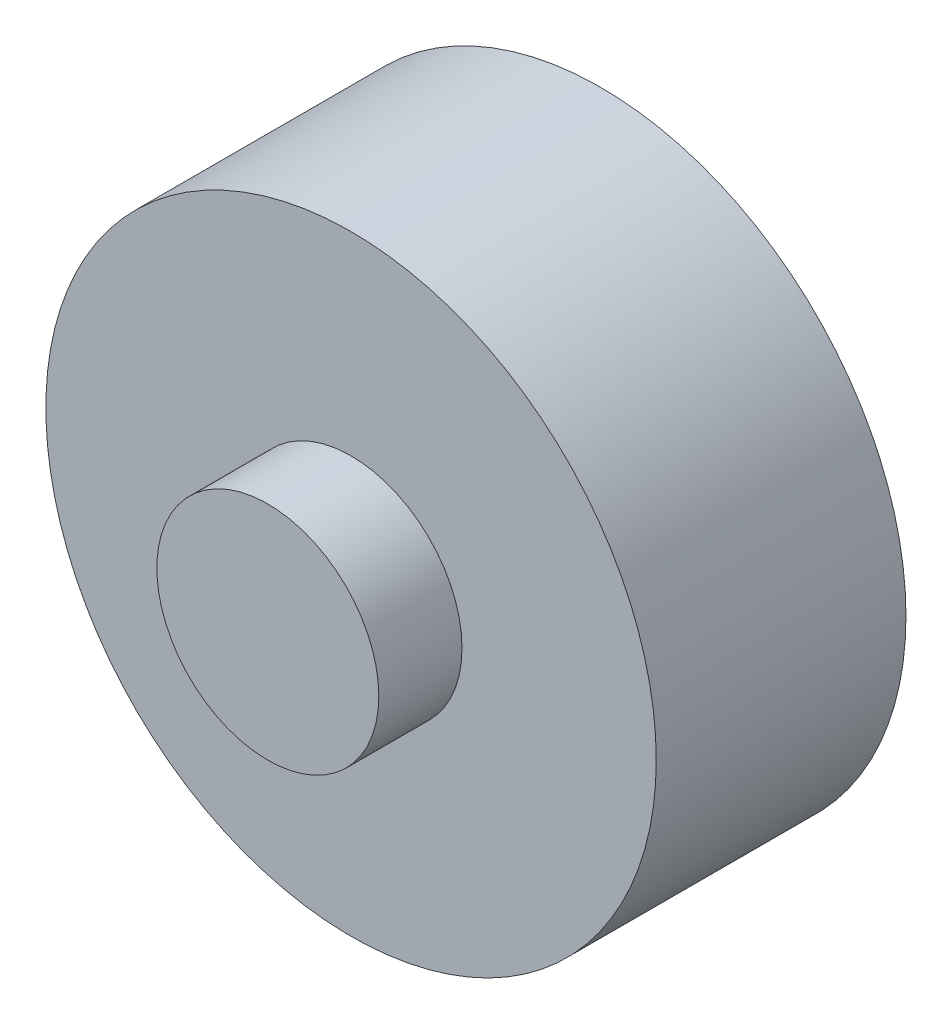
SolidWorks part; units mm, degrees
ref_plane "前视基准面" through (0, 0, 0) normal (0, 0, 1) x (1, 0, 0)
ref_plane "上视基准面" through (0, 0, 0) normal (0, 1, 0) x (1, 0, 0)
ref_plane "右视基准面" through (0, 0, 0) normal (1, 0, 0) x (0, 0, -1)
other "Configuration Table"
sketch "草图1" plane through (0, 0, 0) normal (0, 0, 1) x (1, 0, 0)
  circle A0 centre (0, 0) radius 8
extrude "凸台-拉伸1" add sketch "草图1" along normal blind 24
sketch "草图2" plane through (0, 0, 0) normal (0, 0, 1) x (1, 0, 0)
  circle A0 centre (0, 0) radius 22
extrude "凸台-拉伸2" add sketch "草图2" along normal blind 18
sketch "草图3" plane through (0, 0, 18) normal (0, 0, 1) x (1, 0, 0)
  line L0 (17.0755, 3.8312) -> (18.3379, 4.1145)
  line L1 (18.3379, 4.1145) -> (18.3903, 4.1291)
  line L2 (18.3903, 4.1291) -> (18.5441, 4.1833)
  line L3 (18.5441, 4.1833) -> (18.793, 4.2925)
  line L4 (18.793, 4.2925) -> (19.1289, 4.4711)
  line L5 (19.1289, 4.4711) -> (19.5423, 4.7328)
  line L6 (19.5423, 4.7328) -> (20.0218, 5.09)
  line L7 (20.0218, 5.09) -> (20.5548, 5.5539)
  line L8 (20.5548, 5.5539) -> (21.1275, 6.1342)
  line L9 (21.1275, 6.1342) -> (21.1275, 5.09)
  line L10 (21.1275, 5.09) -> (21.609, 4.1291)
  line L11 (21.609, 4.1291) -> (21.9022, 2.0722)
  line L12 (21.9022, 2.0722) -> (22, 0)
  line L13 (22, 0) -> (21.9511, 1.0361)
  line L14 (21.9511, 1.0361) -> (20.0218, 2.0722)
  line L15 (20.0218, 2.0722) -> (20.0483, 1.5377)
  line L16 (20.0483, 1.5377) -> (19.5743, 1.6589)
  line L17 (19.5743, 1.6589) -> (19.1996, 1.725)
  line L18 (19.1996, 1.725) -> (18.9292, 1.7519)
  line L19 (18.9292, 1.7519) -> (18.7662, 1.7559)
  line L20 (18.7662, 1.7559) -> (18.7119, 1.7536)
  line L21 (18.7119, 1.7536) -> (17.0755, 1.7536)
  line L22 (17.0755, 1.7536) -> (17.3629, 2.1864)
  line L23 (17.3629, 2.1864) -> (17.2845, 2.7376)
  line L24 (17.2845, 2.7376) -> (17.0755, 3.8312)
  line L25 (15.0558, 8.9203) -> (16.169, 9.5798)
  line L26 (16.169, 9.5798) -> (16.2143, 9.6099)
  line L27 (16.2143, 9.6099) -> (16.3438, 9.709)
  line L28 (16.3438, 9.709) -> (16.5467, 9.8897)
  line L29 (16.5467, 9.8897) -> (16.811, 10.1635)
  line L30 (16.811, 10.1635) -> (17.1233, 10.5401)
  line L31 (17.1233, 10.5401) -> (17.4689, 11.0279)
  line L32 (17.4689, 11.0279) -> (17.8325, 11.6338)
  line L33 (17.8325, 11.6338) -> (18.6723, 11.6338)
  line L34 (18.6723, 11.6338) -> (19.3108, 10.5401)
  line L35 (19.3108, 10.5401) -> (20.1104, 8.9203)
  line L36 (20.1104, 8.9203) -> (20.6981, 7.4557)
  line L37 (20.6981, 7.4557) -> (20.5406, 7.8482)
  line L38 (20.5406, 7.8482) -> (19.3108, 7.8482)
  line L39 (19.3108, 7.8482) -> (18.5919, 7.6577)
  line L40 (18.5919, 7.6577) -> (18.1037, 7.6265)
  line L41 (18.1037, 7.6265) -> (17.7269, 7.5735)
  line L42 (17.7269, 7.5735) -> (17.4614, 7.5156)
  line L43 (17.4614, 7.5156) -> (17.3051, 7.4691)
  line L44 (17.3051, 7.4691) -> (17.2541, 7.4501)
  line L45 (17.2541, 7.4501) -> (16.169, 7.4501)
  line L46 (16.169, 7.4501) -> (15.8375, 7.4448)
  line L47 (15.8375, 7.4448) -> (15.5926, 7.9448)
  line L48 (15.5926, 7.9448) -> (15.0558, 8.9203)
  line L49 (11.5624, 13.1362) -> (12.4173, 14.1075)
  line L50 (12.4173, 14.1075) -> (12.4511, 14.15)
  line L51 (12.4511, 14.15) -> (12.5436, 14.2843)
  line L52 (12.5436, 14.2843) -> (12.6808, 14.5189)
  line L53 (12.6808, 14.5189) -> (12.8476, 14.8609)
  line L54 (12.8476, 14.8609) -> (13.0281, 15.3156)
  line L55 (13.0281, 15.3156) -> (13.2061, 15.8864)
  line L56 (13.2061, 15.8864) -> (13.3647, 16.575)
  line L57 (13.3647, 16.575) -> (13.3647, 17.4753)
  line L58 (13.3647, 17.4753) -> (15.0558, 16.0413)
  line L59 (15.0558, 16.0413) -> (15.5563, 15.5563)
  line L60 (15.5563, 15.5563) -> (16.222, 14.8609)
  line L61 (16.222, 14.8609) -> (17.3811, 13.4869)
  line L62 (17.3811, 13.4869) -> (17.1062, 13.8128)
  line L63 (17.1062, 13.8128) -> (16.222, 13.8128)
  line L64 (16.222, 13.8128) -> (15.5563, 13.4869)
  line L65 (15.5563, 13.4869) -> (14.8609, 12.8476)
  line L66 (14.8609, 12.8476) -> (14.5189, 12.6808)
  line L67 (14.5189, 12.6808) -> (14.2843, 12.5436)
  line L68 (14.2843, 12.5436) -> (14.15, 12.4511)
  line L69 (14.15, 12.4511) -> (14.1075, 12.4173)
  line L70 (14.1075, 12.4173) -> (12.4173, 11.0279)
  line L71 (12.4173, 11.0279) -> (13.2624, 11.7226)
  line L72 (13.2624, 11.7226) -> (12.4173, 11.7226)
  line L73 (12.4173, 11.7226) -> (11.5624, 13.1362)
  line L74 (6.9372, 15.8864) -> (7.4501, 16.575)
  line L75 (7.4501, 16.575) -> (7.4691, 17.3051)
  line L76 (7.4691, 17.3051) -> (7.5156, 17.4614)
  line L77 (7.5156, 17.4614) -> (7.5735, 17.7269)
  line L78 (7.5735, 17.7269) -> (7.6265, 18.1037)
  line L79 (7.6265, 18.1037) -> (7.6577, 18.5919)
  line L80 (7.6577, 18.5919) -> (7.6506, 19.1898)
  line L81 (7.6506, 19.1898) -> (7.5886, 19.8937)
  line L82 (7.5886, 19.8937) -> (7.5886, 20.6498)
  line L83 (7.5886, 20.6498) -> (9.3937, 19.8937)
  line L84 (9.3937, 19.8937) -> (9.9878, 19.6021)
  line L85 (9.9878, 19.6021) -> (11.5624, 19.6021)
  line L86 (11.5624, 19.6021) -> (12.3627, 18.1979)
  line L87 (12.3627, 18.1979) -> (11.6338, 17.8325)
  line L88 (11.6338, 17.8325) -> (11.0279, 17.4689)
  line L89 (11.0279, 17.4689) -> (10.5401, 17.1233)
  line L90 (10.5401, 17.1233) -> (10.1635, 16.811)
  line L91 (10.1635, 16.811) -> (9.8897, 16.5467)
  line L92 (9.8897, 16.5467) -> (9.709, 16.3438)
  line L93 (9.709, 16.3438) -> (9.6099, 16.2143)
  line L94 (9.6099, 16.2143) -> (9.5798, 16.169)
  line L95 (9.5798, 16.169) -> (9.5798, 14.5189)
  line L96 (9.5798, 14.5189) -> (8.4369, 15.8864)
  line L97 (8.4369, 15.8864) -> (7.9448, 15.5926)
  line L98 (7.9448, 15.5926) -> (6.9372, 15.8864)
  line L99 (6.9372, 15.8864) -> (6.9372, 16.0663)
  line L100 (1.6329, 17.3051) -> (1.7536, 18.1037)
  line L101 (1.7536, 18.1037) -> (1.7559, 18.7662)
  line L102 (1.7559, 18.7662) -> (1.7519, 18.9292)
  line L103 (1.7519, 18.9292) -> (1.725, 19.1996)
  line L104 (1.725, 19.1996) -> (1.6589, 19.5743)
  line L105 (1.6589, 19.5743) -> (1.5377, 20.0483)
  line L106 (1.5377, 20.0483) -> (1.3462, 20.6147)
  line L107 (1.3462, 20.6147) -> (1.0697, 21.265)
  line L108 (1.0697, 21.265) -> (1.3462, 21.9588)
  line L109 (1.3462, 21.9588) -> (3.4416, 21.9588)
  line L110 (3.4416, 21.9588) -> (4.7973, 21.9588)
  line L111 (4.7973, 21.9588) -> (5.4391, 21.3171)
  line L112 (5.4391, 21.3171) -> (5.4391, 19.8937)
  line L113 (5.4391, 19.8937) -> (5.09, 20.0218)
  line L114 (5.09, 20.0218) -> (4.7328, 19.5423)
  line L115 (4.7328, 19.5423) -> (4.4711, 19.1289)
  line L116 (4.4711, 19.1289) -> (4.2925, 18.793)
  line L117 (4.2925, 18.793) -> (4.1833, 18.5441)
  line L118 (4.1833, 18.5441) -> (4.1291, 18.3903)
  line L119 (4.1291, 18.3903) -> (4.1145, 18.3379)
  line L120 (4.1145, 18.3379) -> (4.1145, 17.3051)
  line L121 (4.1145, 17.3051) -> (3.4416, 17.3051)
  line L122 (3.4416, 17.3051) -> (2.7376, 17.2845)
  line L123 (2.7376, 17.2845) -> (1.6329, 17.3051)
  line L124 (1.6329, 17.3051) -> (1.6329, 17.4237)
  line L125 (-3.8312, 17.3644) -> (-4.1145, 18.9292)
  line L126 (-4.1145, 18.9292) -> (-4.1291, 18.3903)
  line L127 (-4.1291, 18.3903) -> (-4.1833, 18.5441)
  line L128 (-4.1833, 18.5441) -> (-4.1145, 18.9292)
  line L129 (-4.1145, 18.9292) -> (-4.4711, 19.1289)
  line L130 (-4.4711, 19.1289) -> (-4.7328, 19.5423)
  line L131 (-4.7328, 19.5423) -> (-5.09, 20.0218)
  line L132 (-5.09, 20.0218) -> (-5.5539, 20.5548)
  line L133 (-5.5539, 20.5548) -> (-6.1342, 21.1275)
  line L134 (-6.1342, 21.1275) -> (-5.09, 21.1275)
  line L135 (-5.09, 21.1275) -> (-4.1145, 21.6118)
  line L136 (-4.1145, 21.6118) -> (-2.0722, 21.6118)
  line L137 (-2.0722, 21.6118) -> (0, 21.6118)
  line L138 (0, 21.6118) -> (-1.0361, 21.6118)
  line L139 (-1.0361, 21.6118) -> (-2.0722, 21.265)
  line L140 (-2.0722, 21.265) -> (-2.0722, 20.6147)
  line L141 (-2.0722, 20.6147) -> (-2.0722, 18.9292)
  line L142 (-2.0722, 18.9292) -> (-1.725, 19.1996)
  line L143 (-1.725, 19.1996) -> (-1.7519, 18.9292)
  line L144 (-1.7519, 18.9292) -> (-1.7559, 18.7662)
  line L145 (-1.7559, 18.7662) -> (-1.7536, 18.7119)
  line L146 (-1.7536, 18.7119) -> (-1.7536, 17.3644)
  line L147 (-1.7536, 17.3644) -> (-2.1864, 17.3629)
  line L148 (-2.1864, 17.3629) -> (-2.7376, 17.2845)
  line L149 (-2.7376, 17.2845) -> (-3.2861, 17.1887)
  line L150 (-3.2861, 17.1887) -> (-3.8312, 17.3644)
  line L151 (-8.9203, 15.5926) -> (-9.5798, 15.8864)
  line L152 (-9.5798, 15.8864) -> (-9.6099, 16.2143)
  line L153 (-9.6099, 16.2143) -> (-9.709, 16.3438)
  line L154 (-9.709, 16.3438) -> (-9.8897, 16.5467)
  line L155 (-9.8897, 16.5467) -> (-10.1635, 16.811)
  line L156 (-10.1635, 16.811) -> (-10.5401, 17.1233)
  line L157 (-10.5401, 17.1233) -> (-11.0279, 17.4689)
  line L158 (-11.0279, 17.4689) -> (-11.6338, 17.8325)
  line L159 (-11.6338, 17.8325) -> (-11.6338, 18.6723)
  line L160 (-11.6338, 18.6723) -> (-10.5401, 19.766)
  line L161 (-10.5401, 19.766) -> (-8.9203, 20.1104)
  line L162 (-8.9203, 20.1104) -> (-7.3995, 20.4337)
  line L163 (-7.3995, 20.4337) -> (-7.5886, 19.8937)
  line L164 (-7.5886, 19.8937) -> (-7.6506, 19.1898)
  line L165 (-7.6506, 19.1898) -> (-7.6577, 18.5919)
  line L166 (-7.6577, 18.5919) -> (-7.6265, 18.1037)
  line L167 (-7.6265, 18.1037) -> (-7.5735, 17.7269)
  line L168 (-7.5735, 17.7269) -> (-7.5156, 17.4614)
  line L169 (-7.5156, 17.4614) -> (-7.4691, 17.3051)
  line L170 (-7.4691, 17.3051) -> (-7.4501, 17.2541)
  line L171 (-7.4501, 17.2541) -> (-7.4501, 15.5926)
  line L172 (-7.4501, 15.5926) -> (-7.4448, 15.8375)
  line L173 (-7.4448, 15.8375) -> (-7.4501, 15.5926)
  line L174 (-7.4501, 15.5926) -> (-8.9203, 15.5926)
  line L175 (-8.9203, 15.5926) -> (-8.9203, 15.0558)
  line L176 (-13.1362, 11.0279) -> (-14.3165, 12.2082)
  line L177 (-14.3165, 12.2082) -> (-14.15, 12.4511)
  line L178 (-14.15, 12.4511) -> (-14.2843, 12.5436)
  line L179 (-14.2843, 12.5436) -> (-14.5189, 12.6808)
  line L180 (-14.5189, 12.6808) -> (-14.8609, 12.8476)
  line L181 (-14.8609, 12.8476) -> (-15.3156, 13.0281)
  line L182 (-15.3156, 13.0281) -> (-15.8864, 13.2061)
  line L183 (-15.8864, 13.2061) -> (-16.575, 13.3647)
  line L184 (-16.575, 13.3647) -> (-17.4753, 13.3647)
  line L185 (-17.4753, 13.3647) -> (-16.575, 14.4662)
  line L186 (-16.575, 14.4662) -> (-15.8864, 15.2192)
  line L187 (-15.8864, 15.2192) -> (-14.8609, 16.3405)
  line L188 (-14.8609, 16.3405) -> (-14.15, 17.1179)
  line L189 (-14.15, 17.1179) -> (-13.1362, 17.1179)
  line L190 (-13.1362, 17.1179) -> (-13.1362, 16.3405)
  line L191 (-13.1362, 16.3405) -> (-13.1362, 15.2192)
  line L192 (-13.1362, 15.2192) -> (-12.8476, 14.8609)
  line L193 (-12.8476, 14.8609) -> (-12.6808, 14.5189)
  line L194 (-12.6808, 14.5189) -> (-12.5436, 14.2843)
  line L195 (-12.5436, 14.2843) -> (-12.4511, 14.15)
  line L196 (-12.4511, 14.15) -> (-12.4173, 14.1075)
  line L197 (-12.4173, 14.1075) -> (-11.0279, 12.4511)
  line L198 (-11.0279, 12.4511) -> (-11.7226, 13.2793)
  line L199 (-11.7226, 13.2793) -> (-11.7226, 12.4511)
  line L200 (-11.7226, 12.4511) -> (-13.1362, 12.4511)
  line L201 (-13.1362, 12.4511) -> (-13.1362, 11.0279)
  line L202 (-15.8864, 7.4448) -> (-17.4753, 7.9448)
  line L203 (-17.4753, 7.9448) -> (-17.3051, 7.4691)
  line L204 (-17.3051, 7.4691) -> (-17.4614, 7.5156)
  line L205 (-17.4614, 7.5156) -> (-17.7269, 7.5735)
  line L206 (-17.7269, 7.5735) -> (-18.1037, 7.6265)
  line L207 (-18.1037, 7.6265) -> (-18.5919, 7.6577)
  line L208 (-18.5919, 7.6577) -> (-19.1898, 7.6506)
  line L209 (-19.1898, 7.6506) -> (-19.8937, 7.5886)
  line L210 (-19.8937, 7.5886) -> (-20.6498, 7.5886)
  line L211 (-20.6498, 7.5886) -> (-20.1104, 8.9203)
  line L212 (-20.1104, 8.9203) -> (-19.8047, 9.5798)
  line L213 (-19.8047, 9.5798) -> (-19.1335, 11.0279)
  line L214 (-19.1335, 11.0279) -> (-18.2065, 13.0281)
  line L215 (-18.2065, 13.0281) -> (-18.2065, 11.0279)
  line L216 (-18.2065, 11.0279) -> (-17.4753, 11.0279)
  line L217 (-17.4753, 11.0279) -> (-17.1233, 10.5401)
  line L218 (-17.1233, 10.5401) -> (-16.811, 10.1635)
  line L219 (-16.811, 10.1635) -> (-16.5467, 9.8897)
  line L220 (-16.5467, 9.8897) -> (-16.3438, 9.709)
  line L221 (-16.3438, 9.709) -> (-16.2143, 9.6099)
  line L222 (-16.2143, 9.6099) -> (-16.169, 9.5798)
  line L223 (-16.169, 9.5798) -> (-14.5189, 9.5798)
  line L224 (-14.5189, 9.5798) -> (-15.8864, 7.9448)
  line L225 (-15.8864, 7.9448) -> (-15.5926, 7.9448)
  line L226 (-15.5926, 7.9448) -> (-15.8864, 7.4448)
  line L227 (-15.8864, 7.4448) -> (-16.0663, 6.9372)
  line L228 (-17.3051, 1.7536) -> (-18.1037, 1.7536)
  line L229 (-18.1037, 1.7536) -> (-18.7662, 1.7559)
  line L230 (-18.7662, 1.7559) -> (-18.9292, 1.7519)
  line L231 (-18.9292, 1.7519) -> (-19.1996, 1.725)
  line L232 (-19.1996, 1.725) -> (-19.5743, 1.6589)
  line L233 (-19.5743, 1.6589) -> (-20.0483, 1.5377)
  line L234 (-20.0483, 1.5377) -> (-20.6147, 1.3462)
  line L235 (-20.6147, 1.3462) -> (-21.265, 1.0697)
  line L236 (-21.265, 1.0697) -> (-21.9588, 1.3462)
  line L237 (-21.9588, 1.3462) -> (-21.6638, 3.8312)
  line L238 (-21.6638, 3.8312) -> (-21.6118, 4.1145)
  line L239 (-21.6118, 4.1145) -> (-21.2874, 5.5539)
  line L240 (-21.2874, 5.5539) -> (-20.5548, 5.5539)
  line L241 (-20.5548, 5.5539) -> (-20.0218, 5.09)
  line L242 (-20.0218, 5.09) -> (-19.5423, 4.7328)
  line L243 (-19.5423, 4.7328) -> (-19.1289, 4.4711)
  line L244 (-19.1289, 4.4711) -> (-18.793, 4.2925)
  line L245 (-18.793, 4.2925) -> (-18.5441, 4.1833)
  line L246 (-18.5441, 4.1833) -> (-18.3903, 4.1291)
  line L247 (-18.3903, 4.1291) -> (-18.3379, 4.1145)
  line L248 (-18.3379, 4.1145) -> (-17.3051, 4.1145)
  line L249 (-17.3051, 4.1145) -> (-17.3051, 3.8312)
  line L250 (-17.3051, 3.8312) -> (-17.3051, 2.7376)
  line L251 (-17.3051, 2.7376) -> (-17.3051, 1.7536)
  line L252 (-17.3051, 1.7536) -> (-17.4237, 1.6329)
  line L253 (-17.4237, -3.8312) -> (-18.9292, -4.1145)
  line L254 (-18.9292, -4.1145) -> (-18.3903, -4.1291)
  line L255 (-18.3903, -4.1291) -> (-18.5441, -4.1833)
  line L256 (-18.5441, -4.1833) -> (-18.9292, -4.1145)
  line L257 (-18.9292, -4.1145) -> (-19.1289, -4.4711)
  line L258 (-19.1289, -4.4711) -> (-19.5423, -4.7328)
  line L259 (-19.5423, -4.7328) -> (-20.0218, -5.09)
  line L260 (-20.0218, -5.09) -> (-20.5548, -5.5539)
  line L261 (-20.5548, -5.5539) -> (-21.1275, -6.1342)
  line L262 (-21.1275, -6.1342) -> (-21.4031, -5.09)
  line L263 (-21.4031, -5.09) -> (-21.6118, -4.1145)
  line L264 (-21.6118, -4.1145) -> (-21.9022, -2.0722)
  line L265 (-21.9022, -2.0722) -> (-22, 0)
  line L266 (-22, 0) -> (-21.9511, -1.0361)
  line L267 (-21.9511, -1.0361) -> (-21.265, -2.0722)
  line L268 (-21.265, -2.0722) -> (-20.6147, -2.0722)
  line L269 (-20.6147, -2.0722) -> (-18.9292, -2.0722)
  line L270 (-18.9292, -2.0722) -> (-19.1996, -1.725)
  line L271 (-19.1996, -1.725) -> (-18.9292, -1.7519)
  line L272 (-18.9292, -1.7519) -> (-18.7662, -1.7559)
  line L273 (-18.7662, -1.7559) -> (-18.7119, -1.7536)
  line L274 (-18.7119, -1.7536) -> (-17.4237, -1.7536)
  line L275 (-17.4237, -1.7536) -> (-17.3629, -2.1864)
  line L276 (-17.3629, -2.1864) -> (-17.2845, -2.7376)
  line L277 (-17.2845, -2.7376) -> (-17.1887, -3.2861)
  line L278 (-17.1887, -3.2861) -> (-17.4237, -3.8312)
  line L279 (-15.5926, -8.9203) -> (-16.0663, -9.5798)
  line L280 (-16.0663, -9.5798) -> (-16.2143, -9.6099)
  line L281 (-16.2143, -9.6099) -> (-16.3438, -9.709)
  line L282 (-16.3438, -9.709) -> (-16.5467, -9.8897)
  line L283 (-16.5467, -9.8897) -> (-16.811, -10.1635)
  line L284 (-16.811, -10.1635) -> (-17.1233, -10.5401)
  line L285 (-17.1233, -10.5401) -> (-17.4689, -11.0279)
  line L286 (-17.4689, -11.0279) -> (-17.8325, -11.6338)
  line L287 (-17.8325, -11.6338) -> (-18.1979, -12.3627)
  line L288 (-18.1979, -12.3627) -> (-18.6723, -11.6338)
  line L289 (-18.6723, -11.6338) -> (-19.3108, -10.5401)
  line L290 (-19.3108, -10.5401) -> (-20.1104, -8.9203)
  line L291 (-20.1104, -8.9203) -> (-21.1275, -6.8599)
  line L292 (-21.1275, -6.8599) -> (-20.1104, -6.8599)
  line L293 (-20.1104, -6.8599) -> (-19.3108, -7.6506)
  line L294 (-19.3108, -7.6506) -> (-18.5919, -7.6577)
  line L295 (-18.5919, -7.6577) -> (-18.1037, -7.6265)
  line L296 (-18.1037, -7.6265) -> (-17.7269, -7.5735)
  line L297 (-17.7269, -7.5735) -> (-17.4614, -7.5156)
  line L298 (-17.4614, -7.5156) -> (-17.3051, -7.4691)
  line L299 (-17.3051, -7.4691) -> (-17.2541, -7.4501)
  line L300 (-17.2541, -7.4501) -> (-15.5926, -7.4501)
  line L301 (-15.5926, -7.4501) -> (-15.8375, -7.4448)
  line L302 (-15.8375, -7.4448) -> (-15.5926, -7.4501)
  line L303 (-15.5926, -7.4501) -> (-15.5926, -8.9203)
  line L304 (-15.5926, -8.9203) -> (-15.0558, -8.9203)
  line L305 (-11.7226, -13.1362) -> (-13.1362, -14.1075)
  line L306 (-13.1362, -14.1075) -> (-12.4511, -14.15)
  line L307 (-12.4511, -14.15) -> (-12.5436, -14.2843)
  line L308 (-12.5436, -14.2843) -> (-12.6808, -14.5189)
  line L309 (-12.6808, -14.5189) -> (-12.8476, -14.8609)
  line L310 (-12.8476, -14.8609) -> (-13.0281, -15.3156)
  line L311 (-13.0281, -15.3156) -> (-13.2061, -15.8864)
  line L312 (-13.2061, -15.8864) -> (-13.3647, -16.575)
  line L313 (-13.3647, -16.575) -> (-13.3647, -17.3811)
  line L314 (-13.3647, -17.3811) -> (-15.0558, -16.0413)
  line L315 (-15.0558, -16.0413) -> (-15.5563, -15.5563)
  line L316 (-15.5563, -15.5563) -> (-16.8813, -14.1075)
  line L317 (-16.8813, -14.1075) -> (-17.3811, -13.4869)
  line L318 (-17.3811, -13.4869) -> (-17.1312, -13.7972)
  line L319 (-17.1312, -13.7972) -> (-15.5563, -13.7972)
  line L320 (-15.5563, -13.7972) -> (-15.5563, -13.4869)
  line L321 (-15.5563, -13.4869) -> (-14.8609, -12.8476)
  line L322 (-14.8609, -12.8476) -> (-14.5189, -12.6808)
  line L323 (-14.5189, -12.6808) -> (-14.2843, -12.5436)
  line L324 (-14.2843, -12.5436) -> (-14.15, -12.4511)
  line L325 (-14.15, -12.4511) -> (-14.1075, -12.4173)
  line L326 (-14.1075, -12.4173) -> (-13.1362, -11.0279)
  line L327 (-13.1362, -11.0279) -> (-13.1362, -12.4173)
  line L328 (-13.1362, -12.4173) -> (-11.7226, -12.4173)
  line L329 (-11.7226, -12.4173) -> (-11.9744, -12.7618)
  line L330 (-11.9744, -12.7618) -> (-11.7226, -13.1362)
  line L331 (-7.4501, -15.8864) -> (-7.4501, -17.3811)
  line L332 (-7.4501, -17.3811) -> (-7.4691, -17.3051)
  line L333 (-7.4691, -17.3051) -> (-7.4501, -17.3811)
  line L334 (-7.4501, -17.3811) -> (-7.5735, -17.7269)
  line L335 (-7.5735, -17.7269) -> (-7.6265, -18.1037)
  line L336 (-7.6265, -18.1037) -> (-7.6577, -18.5919)
  line L337 (-7.6577, -18.5919) -> (-7.6506, -19.1898)
  line L338 (-7.6506, -19.1898) -> (-7.5886, -19.8937)
  line L339 (-7.5886, -19.8937) -> (-7.5886, -20.6981)
  line L340 (-7.5886, -20.6981) -> (-8.9203, -20.1104)
  line L341 (-8.9203, -20.1104) -> (-9.5798, -19.8047)
  line L342 (-9.5798, -19.8047) -> (-11.7226, -18.8116)
  line L343 (-11.7226, -18.8116) -> (-12.3627, -18.1979)
  line L344 (-12.3627, -18.1979) -> (-11.6338, -17.8325)
  line L345 (-11.6338, -17.8325) -> (-11.0279, -17.4689)
  line L346 (-11.0279, -17.4689) -> (-10.5401, -17.1233)
  line L347 (-10.5401, -17.1233) -> (-10.1635, -16.811)
  line L348 (-10.1635, -16.811) -> (-9.8897, -16.5467)
  line L349 (-9.8897, -16.5467) -> (-9.709, -16.3438)
  line L350 (-9.709, -16.3438) -> (-9.6099, -16.2143)
  line L351 (-9.6099, -16.2143) -> (-9.5798, -16.169)
  line L352 (-9.5798, -16.169) -> (-9.5798, -14.5189)
  line L353 (-9.5798, -14.5189) -> (-8.9203, -15.8864)
  line L354 (-8.9203, -15.8864) -> (-7.4501, -15.8864)
  line L355 (-7.4501, -15.8864) -> (-7.4448, -15.8375)
  line L356 (-7.4448, -15.8375) -> (-7.4501, -15.8864)
  line L357 (-2.1864, -17.3811) -> (-2.1864, -18.1037)
  line L358 (-2.1864, -18.1037) -> (-1.7559, -18.7662)
  line L359 (-1.7559, -18.7662) -> (-1.7519, -18.9292)
  line L360 (-1.7519, -18.9292) -> (-1.725, -19.1996)
  line L361 (-1.725, -19.1996) -> (-1.6589, -19.5743)
  line L362 (-1.6589, -19.5743) -> (-1.5377, -20.0483)
  line L363 (-1.5377, -20.0483) -> (-1.3462, -20.6147)
  line L364 (-1.3462, -20.6147) -> (-1.0697, -21.265)
  line L365 (-1.0697, -21.265) -> (-0.6948, -21.989)
  line L366 (-0.6948, -21.989) -> (-1.3462, -21.9588)
  line L367 (-1.3462, -21.9588) -> (-3.2861, -21.7532)
  line L368 (-3.2861, -21.7532) -> (-4.1291, -21.609)
  line L369 (-4.1291, -21.609) -> (-5.5539, -21.2874)
  line L370 (-5.5539, -21.2874) -> (-5.5539, -20.5548)
  line L371 (-5.5539, -20.5548) -> (-5.09, -20.0218)
  line L372 (-5.09, -20.0218) -> (-4.7328, -19.5423)
  line L373 (-4.7328, -19.5423) -> (-4.4711, -19.1289)
  line L374 (-4.4711, -19.1289) -> (-4.2925, -18.793)
  line L375 (-4.2925, -18.793) -> (-4.1833, -18.5441)
  line L376 (-4.1833, -18.5441) -> (-4.1291, -18.3903)
  line L377 (-4.1291, -18.3903) -> (-4.1145, -18.3379)
  line L378 (-4.1145, -18.3379) -> (-4.1145, -17.3811)
  line L379 (-4.1145, -17.3811) -> (-3.2861, -17.3811)
  line L380 (-3.2861, -17.3811) -> (-2.7376, -17.2845)
  line L381 (-2.7376, -17.2845) -> (-2.1864, -17.3811)
  line L382 (-2.1864, -17.3811) -> (-1.6329, -17.4237)
  line L383 (3.4416, -17.4237) -> (3.4416, -18.9292)
  line L384 (3.4416, -18.9292) -> (4.1291, -18.3903)
  line L385 (4.1291, -18.3903) -> (4.1833, -18.5441)
  line L386 (4.1833, -18.5441) -> (4.2925, -18.793)
  line L387 (4.2925, -18.793) -> (4.4711, -19.1289)
  line L388 (4.4711, -19.1289) -> (4.7328, -19.5423)
  line L389 (4.7328, -19.5423) -> (5.09, -20.0218)
  line L390 (5.09, -20.0218) -> (5.5539, -20.5548)
  line L391 (5.5539, -20.5548) -> (6.1342, -21.1275)
  line L392 (6.1342, -21.1275) -> (5.09, -21.4031)
  line L393 (5.09, -21.4031) -> (3.4416, -21.7291)
  line L394 (3.4416, -21.7291) -> (2.7376, -21.7291)
  line L395 (2.7376, -21.7291) -> (0, -21.7291)
  line L396 (0, -21.7291) -> (1.3688, -21.7291)
  line L397 (1.3688, -21.7291) -> (1.3688, -21.265)
  line L398 (1.3688, -21.265) -> (1.3688, -20.6147)
  line L399 (1.3688, -20.6147) -> (1.3688, -18.9292)
  line L400 (1.3688, -18.9292) -> (1.725, -19.1996)
  line L401 (1.725, -19.1996) -> (1.7519, -18.9292)
  line L402 (1.7519, -18.9292) -> (1.7559, -18.7662)
  line L403 (1.7559, -18.7662) -> (1.7536, -18.7119)
  line L404 (1.7536, -18.7119) -> (1.7536, -17.4237)
  line L405 (1.7536, -17.4237) -> (2.1864, -17.3629)
  line L406 (2.1864, -17.3629) -> (2.7376, -17.2845)
  line L407 (2.7376, -17.2845) -> (3.4416, -17.4237)
  line L408 (3.4416, -17.4237) -> (3.8312, -17.0755)
  line L409 (9.5798, -14.5189) -> (9.5798, -15.8375)
  line L410 (9.5798, -15.8375) -> (9.6099, -16.2143)
  line L411 (9.6099, -16.2143) -> (9.709, -16.3438)
  line L412 (9.709, -16.3438) -> (9.8897, -16.5467)
  line L413 (9.8897, -16.5467) -> (10.1635, -16.811)
  line L414 (10.1635, -16.811) -> (10.5401, -17.1233)
  line L415 (10.5401, -17.1233) -> (11.0279, -17.4689)
  line L416 (11.0279, -17.4689) -> (11.6338, -17.8325)
  line L417 (11.6338, -17.8325) -> (12.3627, -18.1979)
  line L418 (12.3627, -18.1979) -> (11.6338, -19.5423)
  line L419 (11.6338, -19.5423) -> (10.1045, -19.5423)
  line L420 (10.1045, -19.5423) -> (8.4369, -20.318)
  line L421 (8.4369, -20.318) -> (7.9448, -20.318)
  line L422 (7.9448, -20.318) -> (7.5886, -19.8937)
  line L423 (7.5886, -19.8937) -> (7.6506, -19.1898)
  line L424 (7.6506, -19.1898) -> (7.6577, -18.5919)
  line L425 (7.6577, -18.5919) -> (7.6265, -18.1037)
  line L426 (7.6265, -18.1037) -> (7.5735, -17.7269)
  line L427 (7.5735, -17.7269) -> (7.5156, -17.4614)
  line L428 (7.5156, -17.4614) -> (7.4691, -17.3051)
  line L429 (7.4691, -17.3051) -> (7.4501, -17.2541)
  line L430 (7.4501, -17.2541) -> (7.4501, -15.8375)
  line L431 (7.4501, -15.8375) -> (7.4448, -15.8375)
  line L432 (7.4448, -15.8375) -> (7.4501, -15.8375)
  line L433 (7.4501, -15.8375) -> (7.9448, -15.8375)
  line L434 (7.9448, -15.8375) -> (9.5798, -14.5189)
  line L435 (12.4173, -11.0279) -> (14.1075, -13.1238)
  line L436 (14.1075, -13.1238) -> (14.15, -12.4511)
  line L437 (14.15, -12.4511) -> (14.2843, -12.5436)
  line L438 (14.2843, -12.5436) -> (14.5189, -12.6808)
  line L439 (14.5189, -12.6808) -> (14.8609, -12.8476)
  line L440 (14.8609, -12.8476) -> (15.3156, -13.0281)
  line L441 (15.3156, -13.0281) -> (15.8864, -13.2061)
  line L442 (15.8864, -13.2061) -> (16.575, -13.3647)
  line L443 (16.575, -13.3647) -> (17.0755, -13.3647)
  line L444 (17.0755, -13.3647) -> (16.575, -14.4662)
  line L445 (16.575, -14.4662) -> (15.8864, -15.2192)
  line L446 (15.8864, -15.2192) -> (14.1075, -16.8813)
  line L447 (14.1075, -16.8813) -> (13.4869, -17.3811)
  line L448 (13.4869, -17.3811) -> (13.7972, -17.1312)
  line L449 (13.7972, -17.1312) -> (13.7972, -15.2192)
  line L450 (13.7972, -15.2192) -> (13.4869, -15.2192)
  line L451 (13.4869, -15.2192) -> (12.8476, -14.8609)
  line L452 (12.8476, -14.8609) -> (12.6808, -14.5189)
  line L453 (12.6808, -14.5189) -> (12.5436, -14.2843)
  line L454 (12.5436, -14.2843) -> (12.4511, -14.15)
  line L455 (12.4511, -14.15) -> (12.4173, -14.1075)
  line L456 (12.4173, -14.1075) -> (11.0279, -13.1238)
  line L457 (11.0279, -13.1238) -> (12.4173, -13.1238)
  line L458 (12.4173, -13.1238) -> (12.4173, -12.4511)
  line L459 (12.4173, -12.4511) -> (12.7618, -11.9744)
  line L460 (12.7618, -11.9744) -> (13.1362, -11.5624)
  line L461 (15.8864, -7.4501) -> (16.575, -7.4501)
  line L462 (16.575, -7.4501) -> (17.3051, -7.4691)
  line L463 (17.3051, -7.4691) -> (17.4614, -7.5156)
  line L464 (17.4614, -7.5156) -> (17.7269, -7.5735)
  line L465 (17.7269, -7.5735) -> (18.1037, -7.6265)
  line L466 (18.1037, -7.6265) -> (18.5919, -7.6577)
  line L467 (18.5919, -7.6577) -> (19.1898, -7.6506)
  line L468 (19.1898, -7.6506) -> (19.8937, -7.5886)
  line L469 (19.8937, -7.5886) -> (20.0483, -7.5886)
  line L470 (20.0483, -7.5886) -> (19.8937, -9.3937)
  line L471 (19.8937, -9.3937) -> (19.6021, -9.9878)
  line L472 (19.6021, -9.9878) -> (19.6021, -11.5624)
  line L473 (19.6021, -11.5624) -> (18.5919, -11.7619)
  line L474 (18.5919, -11.7619) -> (18.1037, -11.7619)
  line L475 (18.1037, -11.7619) -> (17.4689, -11.0279)
  line L476 (17.4689, -11.0279) -> (17.1233, -10.5401)
  line L477 (17.1233, -10.5401) -> (16.811, -10.1635)
  line L478 (16.811, -10.1635) -> (16.5467, -9.8897)
  line L479 (16.5467, -9.8897) -> (16.3438, -9.709)
  line L480 (16.3438, -9.709) -> (16.2143, -9.6099)
  line L481 (16.2143, -9.6099) -> (16.169, -9.5798)
  line L482 (16.169, -9.5798) -> (14.5189, -9.5798)
  line L483 (14.5189, -9.5798) -> (15.8864, -8.9203)
  line L484 (15.8864, -8.9203) -> (15.8864, -7.4501)
  line L485 (15.8864, -7.4501) -> (15.8375, -7.4448)
  line L486 (15.8375, -7.4448) -> (15.8864, -7.4501)
  line L487 (17.0755, -2.1864) -> (19.1996, -2.1864)
  line L488 (19.1996, -2.1864) -> (18.7662, -1.7559)
  line L489 (18.7662, -1.7559) -> (18.9292, -1.7519)
  line L490 (18.9292, -1.7519) -> (19.1996, -1.725)
  line L491 (19.1996, -1.725) -> (19.5743, -1.6589)
  line L492 (19.5743, -1.6589) -> (20.0483, -1.5377)
  line L493 (20.0483, -1.5377) -> (20.6147, -1.3462)
  line L494 (20.6147, -1.3462) -> (21.265, -1.0697)
  line L495 (21.265, -1.0697) -> (22, 0)
  line L496 (22, 0) -> (22, -1.3462)
  line L497 (22, -1.3462) -> (21.7532, -3.2861)
  line L498 (21.7532, -3.2861) -> (21.609, -4.1291)
  line L499 (21.609, -4.1291) -> (21.609, -6.8599)
  line L500 (21.609, -6.8599) -> (20.4289, -5.6798)
  line L501 (20.4289, -5.6798) -> (20.0218, -5.09)
  line L502 (20.0218, -5.09) -> (19.5423, -4.7328)
  line L503 (19.5423, -4.7328) -> (19.1289, -4.4711)
  line L504 (19.1289, -4.4711) -> (18.793, -4.2925)
  line L505 (18.793, -4.2925) -> (18.5441, -4.1833)
  line L506 (18.5441, -4.1833) -> (18.3903, -4.1291)
  line L507 (18.3903, -4.1291) -> (18.3379, -4.1145)
  line L508 (18.3379, -4.1145) -> (17.0755, -4.1145)
  line L509 (17.0755, -4.1145) -> (17.0755, -3.2861)
  line L510 (17.0755, -3.2861) -> (17.2845, -2.7376)
  line L511 (17.2845, -2.7376) -> (17.0755, -2.1864)
  line L512 (17.0755, -2.1864) -> (17.4237, -1.6329)
  circle A0 centre (0, 0) radius 22 construction
